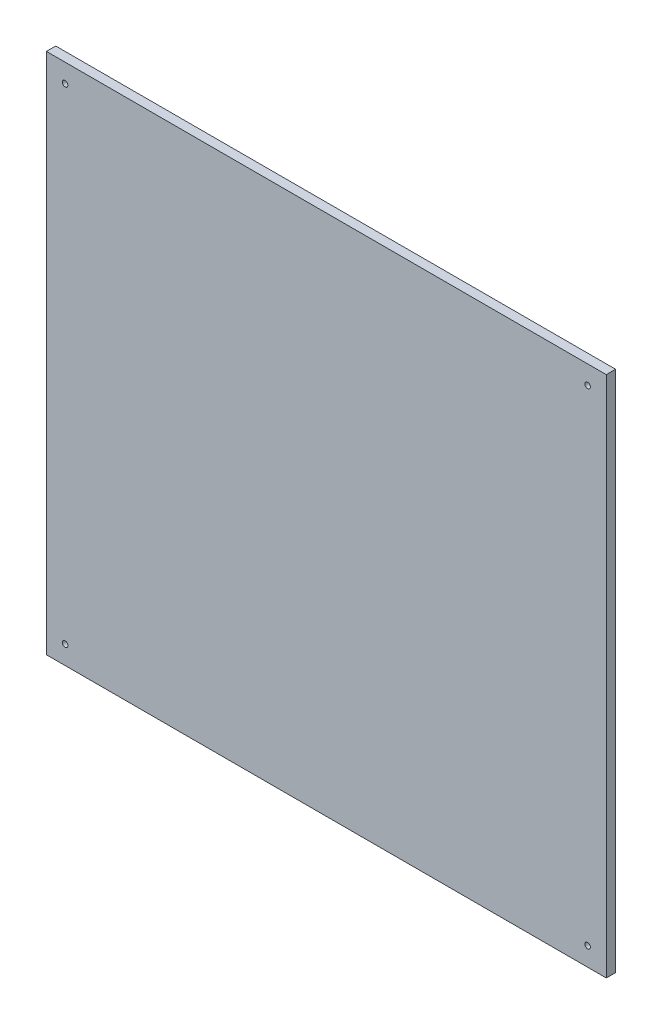
SolidWorks part; units mm, degrees
ref_plane "Plan de face" through (0, 0, 0) normal (0, 0, 1) x (1, 0, 0)
ref_plane "Plan de dessus" through (0, 0, 0) normal (0, 1, 0) x (1, 0, 0)
ref_plane "Plan de droite" through (0, 0, 0) normal (1, 0, 0) x (0, 0, -1)
sketch "Esquisse1" plane through (0, 0, 0) normal (0, 0, 1) x (1, 0, 0)
  line L1 (0, 0) -> (300, 0)
  line L2 (0, 0) -> (0, 280)
  line L3 (0, 280) -> (300, 280)
  line L4 (300, 0) -> (300, 280)
  dimension "D1" = 280
  dimension "D2" = 300
extrude "Boss.-Extru.1" add sketch "Esquisse1" along normal blind 5
sketch "Esquisse2" plane through (0, 0, 0) normal (0, 0, 1) x (1, 0, 0)
  line L0 (0, 0) -> (300, 0) construction
  line L1 (0, 280) -> (0, 0) construction
  line L2 (300, 280) -> (0, 280) construction
  line L3 (300, 0) -> (300, 280) construction
  circle A0 centre (10, 270) radius 1.5
  circle A1 centre (290, 270) radius 1.5
  circle A2 centre (290, 10) radius 1.5
  circle A3 centre (10, 10) radius 1.5
  dimension "D1" = 3
  dimension "D2" = 3
  dimension "D3" = 3
  dimension "D4" = 3
  dimension "D5" = 10
  dimension "D6" = 10
  dimension "D7" = 10
  dimension "D8" = 10
  dimension "D9" = 10
  dimension "D10" = 10
  dimension "D11" = 10
  dimension "D12" = 10
extrude "Enlèv. mat.-Extru.1" cut sketch "Esquisse2" along normal through all
